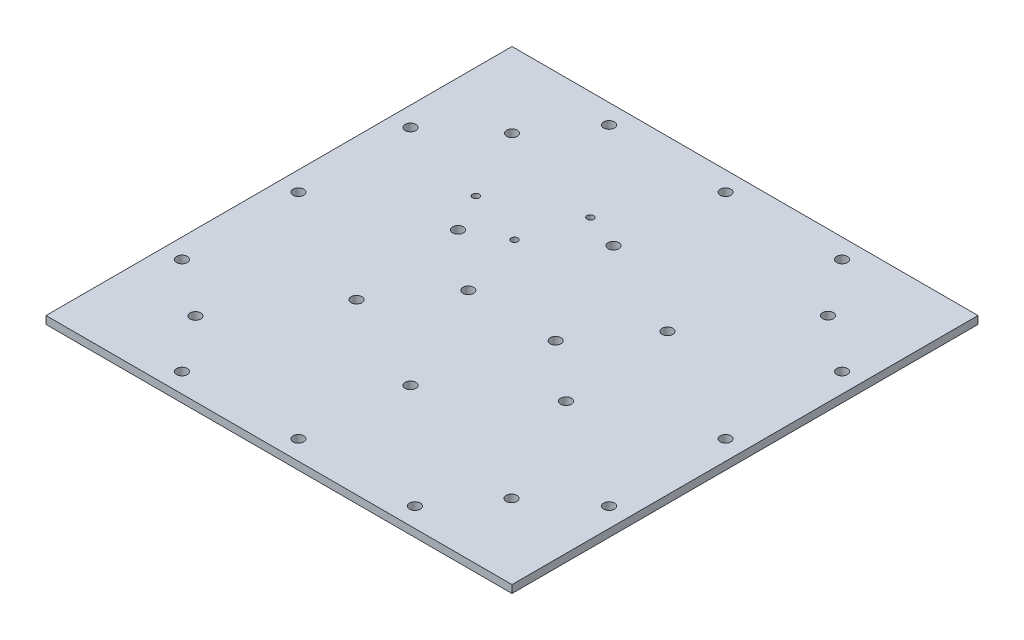
SolidWorks part; units mm, degrees
material "6061-T6 (SS)"
ref_plane "Front Plane" through (0, 0, 0) normal (0, 0, 1) x (1, 0, 0)
ref_plane "Top Plane" through (0, 0, 0) normal (0, 1, 0) x (1, 0, 0)
ref_plane "Right Plane" through (0, 0, 0) normal (1, 0, 0) x (0, 0, -1)
sketch "Sketch1" plane through (0, 0, 0) normal (0, 1, 0) x (1, 0, 0)
  line L8 (0, 200) -> (200, 0) construction
  line L9 (0, 0) -> (200, 0)
  line L10 (0, 0) -> (0, 200)
  line L11 (0, 200) -> (200, 200)
  line L12 (200, 0) -> (200, 200)
  line L13 (-20, -20) -> (220, -20)
  line L14 (-20, -20) -> (-20, 220)
  line L15 (-20, 220) -> (220, 220)
  line L16 (220, -20) -> (220, 220)
  line L17 (-10, -10) -> (210, -10) construction
  line L18 (-10, -10) -> (-10, 210) construction
  line L23 (-10, 210) -> (210, 210) construction
  line L24 (210, -10) -> (210, 210) construction
  point P4 (40, 210)
  point P9 (160, 210)
  point P14 (100, 100)
  point P18 (100, 210)
  point P19 (210, 160)
  point P20 (210, 40)
  point P21 (210, 100)
  point P22 (160, -10)
  point P23 (40, -10)
  point P24 (100, -10)
  point P25 (-10, 40)
  point P26 (-10, 160)
  point P28 (-10, 100)
  point P29 (100, 100)
  dimension "D1" = 200
  dimension "D2" = 200
  dimension "D4" = 10
  dimension "D5" = 10
  dimension "D6" = 10
  dimension "D7" = 10
  dimension "D8" = 10
  dimension "D9" = 10
  dimension "D3" = 240
  dimension "D10" = 240
  dimension "D11" = 60
  dimension "D12" = 60
  dimension "D13" = 4
extrude "Boss-Extrude1" add sketch "Sketch1" along normal blind 4
sketch "Sketch2" plane through (0, 4, 0) normal (0, 1, 0) x (1, 0, 0)
  line L0 (220, -20) -> (220, 220) construction
  line L1 (-20, 220) -> (220, -20) construction
  line L2 (100, 100) -> (100, 220) construction
  line L3 (-20, 220) -> (220, 220) construction
  line L4 (-20, 220) -> (220, 220) construction
  line L5 (-20, -20) -> (-20, 220) construction
  line L6 (100, 100) -> (89.5014, 220) construction
  line L7 (-20, -20) -> (220, -20) construction
  circle A0 centre (18.6827, 181.3173) radius 2.6
  circle A1 centre (181.4368, 181.3173) radius 2.6
  circle A4 centre (181.4368, 18.3) radius 2.6
  circle A5 centre (18.6827, 18.3) radius 2.6
  point P10 (94.9885, 157.2812)
  point P15 (77.5, 100)
  point P16 (122.5, 100)
  point P26 (37.3783, 144.0049)
  point P27 (76.4406, 163.9081)
  point P28 (66.8611, 134.4254)
  point P31 (100, 100)
  point P32 (147.1012, 132.9806)
  point P36 (152.1127, 75.6994)
  point P37 (105.0115, 42.7188)
  point P38 (52.8988, 67.0194)
  point P39 (47.8873, 124.3006)
  point P40 (100, 100)
  dimension "D5" = 5.2
  dimension "D6" = 5.2
  dimension "D7" = 38.3
  dimension "D8" = 38.5632
  dimension "D1" = 5.2
  dimension "D2" = 5.2
  dimension "D3" = 38.6827
  dimension "D4" = 38.6827
  dimension "D9" = 22.5
  dimension "D10" = 22.5
  dimension "D11" = 57.2812
  dimension "D12" = 5
  dimension "D13" = 6
sketch "Sketch3" plane through (0, 4, 0) normal (0, 1, 0) x (1, 0, 0)
  line L0 (-10, -10) -> (-10, 210) construction
  point P0 (18.6827, 181.3173)
  point P3 (181.4368, 181.3173)
  point P6 (181.4368, 18.3)
  point P9 (18.6827, 18.3)
  point P12 (40, 210)
  point P15 (100, 210)
  point P18 (160, 210)
  point P21 (210, 160)
  point P24 (210, 100)
  point P27 (210, 40)
  point P30 (160, -10)
  point P33 (100, -10)
  point P36 (40, -10)
  point P39 (-10, 40)
  point P42 (-10, 100)
  point P45 (-10, 157.7351)
  point P50 (94.9885, 157.2812)
  point P53 (47.8873, 124.3006)
  point P56 (105.0115, 42.7188)
  point P59 (147.1012, 132.9806)
  point P62 (152.1127, 75.6994)
  point P65 (52.8988, 67.0194)
  point P68 (77.5, 100)
  point P71 (122.5, 100)
hole_wizard "M5 Clearance Hole1" positions "Sketch3" profile "Sketch4" hole size "M5" standard "ANSI Metric" end condition through all
sketch "Sketch4" plane through (18.6827, 4, -181.3173) normal (1, 0, 0) x (0, 0, 1)
  line L0 (0, 0) -> (0, 4)
  line L1 (0, 4) -> (2.75, 4)
  line L2 (2.75, 4) -> (2.75, 0)
  line L5 (2.75, 0) -> (0, 0)
  line L11 (0, -6.35) -> (0, 107.95) construction
  dimension "Thru Hole Dia." = 5.5
  dimension "Thru Hole Depth" = 4
sketch "Sketch5" plane through (0, 4, 0) normal (0, 1, 0) x (1, 0, 0)
  point P0 (37.3783, 144.0049)
  point P3 (76.4406, 163.9081)
  point P6 (66.8611, 134.4254)
hole_wizard "M3 Clearance Hole1" positions "Sketch5" profile "Sketch6" hole size "M3" standard "ANSI Metric" end condition through all
sketch "Sketch6" plane through (37.3783, 4, -144.0049) normal (1, 0, 0) x (0, 0, 1)
  line L0 (0, 0) -> (0, 4)
  line L1 (0, 4) -> (1.7, 4)
  line L2 (1.7, 4) -> (1.7, 0)
  line L5 (1.7, 0) -> (0, 0)
  line L11 (0, -6.35) -> (0, 107.95) construction
  dimension "Thru Hole Dia." = 3.4
  dimension "Thru Hole Depth" = 4
equation "\"D11@Sketch1\"=0.25*\"D3@Sketch1\""
equation "\"D12@Sketch1\"=0.25*\"D3@Sketch1\""
